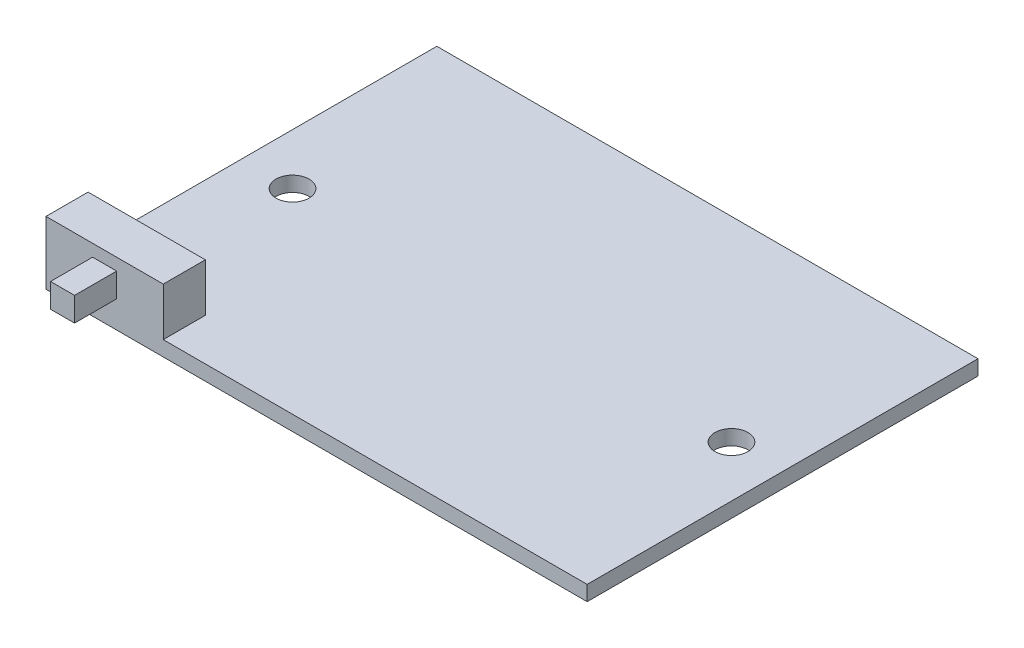
SolidWorks part; units mm, degrees
ref_plane "Front Plane" through (0, 0, 0) normal (0, 0, 1) x (1, 0, 0)
ref_plane "Top Plane" through (0, 0, 0) normal (0, 1, 0) x (1, 0, 0)
ref_plane "Right Plane" through (0, 0, 0) normal (1, 0, 0) x (0, 0, -1)
sketch "Sketch1" plane through (0, 0, 0) normal (0, 1, 0) x (1, 0, 0)
  line L0 (22.86, 0) -> (-22.86, 0) construction
  line L1 (-22.86, 16.51) -> (22.86, 16.51)
  line L2 (-22.86, 16.51) -> (-22.86, -16.51)
  line L3 (-22.86, -16.51) -> (22.86, -16.51)
  line L4 (22.86, 16.51) -> (22.86, -16.51)
  line L5 (-22.86, 16.51) -> (22.86, -16.51) construction
  line L6 (-22.86, -16.51) -> (22.86, 16.51) construction
  line L7 (0, -16.51) -> (0, 16.51) construction
  circle A0 centre (-18.542, 0) radius 1.397
  circle A1 centre (18.542, 0) radius 1.397
  point P0 (0, 0)
  dimension "D3" = 2.794
  dimension "D4" = 37.084
  dimension "D1" = 45.72
  dimension "D2" = 33.02
extrude "Boss-Extrude1" add sketch "Sketch1" along normal blind 1.27
sketch "Sketch3" plane through (0, 1.27, 0) normal (0, 1, 0) x (1, 0, 0)
  line L1 (-22.86, -12.954) -> (-12.954, -12.954)
  line L2 (-22.86, -12.954) -> (-22.86, -16.51)
  line L3 (-22.86, -16.51) -> (-12.954, -16.51)
  line L4 (-12.954, -12.954) -> (-12.954, -16.51)
  point P4 (0, 0)
  dimension "D1" = 3.556
  dimension "D2" = 9.906
extrude "Boss-Extrude2" add sketch "Sketch3" along normal blind 4.064
sketch "Sketch4" plane through (0, 0, 16.51) normal (0, 0, 1) x (1, 0, 0)
  line L0 (-12.954, 1.27) -> (-22.86, 1.27) construction
  line L1 (-18.923, 4.318) -> (-16.891, 4.318)
  line L2 (-18.923, 4.318) -> (-18.923, 2.286)
  line L3 (-18.923, 2.286) -> (-16.891, 2.286)
  line L4 (-16.891, 4.318) -> (-16.891, 2.286)
  line L5 (-12.954, 1.27) -> (-22.86, 1.27) construction
  line L6 (-22.86, 1.27) -> (-12.954, 5.334) construction
  line L7 (-18.923, 2.286) -> (-16.891, 4.318) construction
  point P8 (-17.907, 3.302)
  point P9 (-17.907, 3.302)
  point P10 (0, 0)
  dimension "D1" = 2.032
  dimension "D2" = 2.032
extrude "Boss-Extrude3" add sketch "Sketch4" along normal blind 3.556
